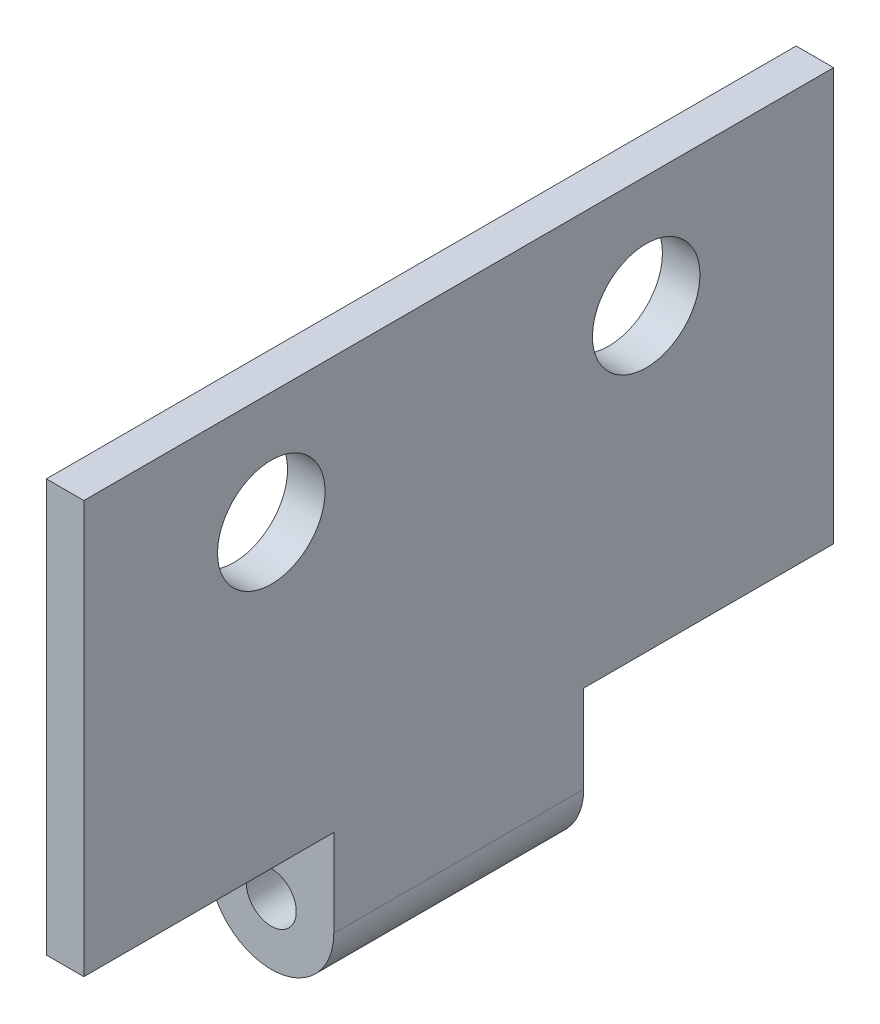
SolidWorks part; units mm, degrees
ref_plane "Front Plane" through (0, 0, 0) normal (0, 0, 1) x (1, 0, 0)
ref_plane "Top Plane" through (0, 0, 0) normal (0, 1, 0) x (1, 0, 0)
ref_plane "Right Plane" through (0, 0, 0) normal (1, 0, 0) x (0, 0, -1)
sketch "Sketch2" plane through (0, 0, 0) normal (0, 0, 1) x (1, 0, 0)
  line L0 (1, 3.5) -> (1, 20)
  line L1 (2.5, 0) -> (2.5, 20)
  line L2 (1, 20) -> (2.5, 20)
  circle A0 centre (0, 0) radius 1
  arc A1 (0, 2.5) -> (2.5, 0) centre (0, 0) ccw
  arc A2 (1, 3.5) -> (0, 2.5) centre (0, 3.5) cw
  dimension "D1" = 2
  dimension "D2" = 5
  dimension "D4" = 1
  dimension "D3" = 20
extrude "Boss-Extrude2" add sketch "Sketch2" along normal blind 30
sketch "Sketch3" plane through (1, 0, 0) normal (-1, 0, 0) x (0, 0, 1)
  line L0 (30, 3.5) -> (0, 3.5) construction
  line L1 (30, 20) -> (30, 3.5) construction
  line L2 (0, 20) -> (0, 3.5) construction
  line L3 (0, 2.5) -> (0, -2.5) construction
  line L4 (0, -3.5) -> (10, -3.5)
  line L5 (0, -3.5) -> (0, 3.5)
  line L6 (0, 3.5) -> (10, 3.5)
  line L7 (10, -3.5) -> (10, 3.5)
  line L8 (0, -3.5) -> (10, 3.5) construction
  line L9 (0, 3.5) -> (10, -3.5) construction
  line L10 (30, -3.5) -> (20, -3.5)
  line L11 (30, -3.5) -> (30, 3.5)
  line L12 (30, 3.5) -> (20, 3.5)
  line L13 (20, -3.5) -> (20, 3.5)
  line L14 (30, -3.5) -> (20, 3.5) construction
  line L15 (30, 3.5) -> (20, -3.5) construction
  circle A0 centre (7.5, 15.5) radius 2.15
  circle A1 centre (22.5, 15.5) radius 2.15
  point P8 (5, 0)
  point P15 (25, 0)
  dimension "D1" = 4.3
  dimension "D2" = 4.3
  dimension "D3" = 15
  dimension "D4" = 7.5
  dimension "D5" = 12
  dimension "D6" = 7.5
  dimension "D7" = 10
  dimension "D8" = 7
  dimension "D9" = 5
  dimension "D10" = 10
  dimension "D11" = 5
  dimension "D12" = 7
extrude "Cut-Extrude1" cut sketch "Sketch3" against normal through all both and the other way through all
